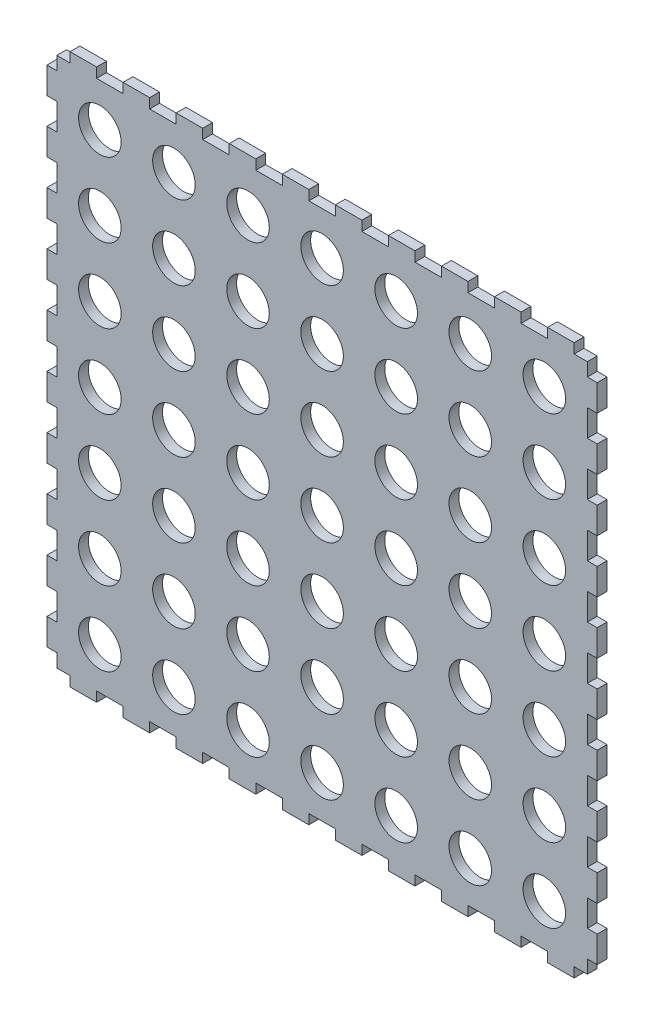
SolidWorks part; units mm, degrees
ref_plane "Front Plane" through (0, 0, 0) normal (0, 0, 1) x (1, 0, 0)
ref_plane "Top Plane" through (0, 0, 0) normal (0, 1, 0) x (1, 0, 0)
ref_plane "Right Plane" through (0, 0, 0) normal (1, 0, 0) x (0, 0, -1)
sketch "Model" plane through (0, 0, 0) normal (0, 0, 1) x (1, 0, 0)
  line L0 (-349.25, 5.6) -> (-349.25, -350) construction
  line L1 (6.35, 5.6) -> (-349.25, 5.6) construction
  line L2 (6.35, -350) -> (6.35, 5.6) construction
  line L3 (-349.25, -350) -> (6.35, -350) construction
  line L4 (-349.25, -350) -> (6.35, 5.6) construction
  line L5 (-350, -172.2) -> (5.6, -172.2) construction
  line L6 (-171.45, -172.581) -> (-171.45, 55.4884) construction
  line L7 (-349.25, -0.75) -> (0, -0.75) construction
  line L8 (-342.9, -343.65) -> (-342.9, 5.6) construction
  line L9 (-349.25, -343.65) -> (0, -343.65) construction
  line L10 (0, -350) -> (0, 5.6) construction
  line L11 (-342.9, -0.75) -> (-334.3275, -0.75)
  line L12 (-334.3275, -0.75) -> (-334.3275, 5.6)
  line L13 (-334.3275, 5.6) -> (-317.1825, 5.6)
  line L14 (-317.1825, 5.6) -> (-317.1825, -0.75)
  line L15 (-317.1825, -0.75) -> (-300.0375, -0.75)
  line L16 (-300.0375, -0.75) -> (-300.0375, 5.6)
  line L17 (-300.0375, 5.6) -> (-282.8925, 5.6)
  line L18 (-282.8925, 5.6) -> (-282.8925, -0.75)
  line L19 (-282.8925, -0.75) -> (-265.7475, -0.75)
  line L20 (-265.7475, -0.75) -> (-265.7475, 5.6)
  line L21 (-265.7475, 5.6) -> (-248.6025, 5.6)
  line L22 (-248.6025, 5.6) -> (-248.6025, -0.75)
  line L23 (-248.6025, -0.75) -> (-231.4575, -0.75)
  line L24 (-231.4575, -0.75) -> (-231.4575, 5.6)
  line L25 (-231.4575, 5.6) -> (-214.3125, 5.6)
  line L26 (-214.3125, 5.6) -> (-214.3125, -0.75)
  line L27 (-214.3125, -0.75) -> (-197.1675, -0.75)
  line L28 (-197.1675, -0.75) -> (-197.1675, 5.6)
  line L29 (-197.1675, 5.6) -> (-180.0225, 5.6)
  line L30 (-180.0225, 5.6) -> (-180.0225, -0.75)
  line L31 (-180.0225, -0.75) -> (-162.8775, -0.75)
  line L32 (-162.8775, -0.75) -> (-162.8775, 5.6)
  line L33 (-162.8775, 5.6) -> (-145.7325, 5.6)
  line L34 (-145.7325, 5.6) -> (-145.7325, -0.75)
  line L35 (-145.7325, -0.75) -> (-128.5875, -0.75)
  line L36 (-128.5875, -0.75) -> (-128.5875, 5.6)
  line L37 (-128.5875, 5.6) -> (-111.4425, 5.6)
  line L38 (-111.4425, 5.6) -> (-111.4425, -0.75)
  line L39 (-111.4425, -0.75) -> (-94.2975, -0.75)
  line L40 (-94.2975, -0.75) -> (-94.2975, 5.6)
  line L41 (-94.2975, 5.6) -> (-77.1525, 5.6)
  line L42 (-77.1525, 5.6) -> (-77.1525, -0.75)
  line L43 (-77.1525, -0.75) -> (-60.0075, -0.75)
  line L44 (-60.0075, -0.75) -> (-60.0075, 5.6)
  line L45 (-60.0075, 5.6) -> (-42.8625, 5.6)
  line L46 (-42.8625, 5.6) -> (-42.8625, -0.75)
  line L47 (-42.8625, -0.75) -> (-25.7175, -0.75)
  line L48 (-25.7175, -0.75) -> (-25.7175, 5.6)
  line L49 (-25.7175, 5.6) -> (-8.5725, 5.6)
  line L50 (-8.5725, 5.6) -> (-8.5725, -0.75)
  line L51 (-8.5725, -0.75) -> (0, -0.75)
  line L52 (-342.9, -0.75) -> (-342.9, -9.3225)
  line L53 (-342.9, -9.3225) -> (-349.25, -9.3225)
  line L54 (-349.25, -9.3225) -> (-349.25, -26.4675)
  line L55 (-349.25, -26.4675) -> (-342.9, -26.4675)
  line L56 (-342.9, -26.4675) -> (-342.9, -43.6125)
  line L57 (-342.9, -43.6125) -> (-349.25, -43.6125)
  line L58 (-349.25, -43.6125) -> (-349.25, -60.7575)
  line L59 (-349.25, -60.7575) -> (-342.9, -60.7575)
  line L60 (-342.9, -60.7575) -> (-342.9, -77.9025)
  line L61 (-342.9, -77.9025) -> (-349.25, -77.9025)
  line L62 (-349.25, -77.9025) -> (-349.25, -95.0475)
  line L63 (-349.25, -95.0475) -> (-342.9, -95.0475)
  line L64 (-342.9, -95.0475) -> (-342.9, -112.1925)
  line L65 (-342.9, -112.1925) -> (-349.25, -112.1925)
  line L66 (-349.25, -112.1925) -> (-349.25, -129.3375)
  line L67 (-349.25, -129.3375) -> (-342.9, -129.3375)
  line L68 (-342.9, -129.3375) -> (-342.9, -146.4825)
  line L69 (-342.9, -146.4825) -> (-349.25, -146.4825)
  line L70 (-349.25, -146.4825) -> (-349.25, -163.6275)
  line L71 (-349.25, -163.6275) -> (-342.9, -163.6275)
  line L72 (-342.9, -163.6275) -> (-342.9, -180.7725)
  line L73 (-342.9, -180.7725) -> (-349.25, -180.7725)
  line L74 (-349.25, -180.7725) -> (-349.25, -197.9175)
  line L75 (-349.25, -197.9175) -> (-342.9, -197.9175)
  line L76 (-342.9, -197.9175) -> (-342.9, -215.0625)
  line L77 (-342.9, -215.0625) -> (-349.25, -215.0625)
  line L78 (-349.25, -215.0625) -> (-349.25, -232.2075)
  line L79 (-349.25, -232.2075) -> (-342.9, -232.2075)
  line L80 (-342.9, -232.2075) -> (-342.9, -249.3525)
  line L81 (-342.9, -249.3525) -> (-349.25, -249.3525)
  line L82 (-349.25, -249.3525) -> (-349.25, -266.4975)
  line L83 (-349.25, -266.4975) -> (-342.9, -266.4975)
  line L84 (-342.9, -266.4975) -> (-342.9, -283.6425)
  line L85 (-342.9, -283.6425) -> (-349.25, -283.6425)
  line L86 (-349.25, -283.6425) -> (-349.25, -300.7875)
  line L87 (-349.25, -300.7875) -> (-342.9, -300.7875)
  line L88 (-342.9, -300.7875) -> (-342.9, -317.9325)
  line L89 (-342.9, -317.9325) -> (-349.25, -317.9325)
  line L90 (-349.25, -317.9325) -> (-349.25, -335.0775)
  line L91 (-349.25, -335.0775) -> (-342.9, -335.0775)
  line L92 (-342.9, -335.0775) -> (-342.9, -343.65)
  line L93 (-342.9, -343.65) -> (-334.3275, -343.65)
  line L94 (-334.3275, -343.65) -> (-334.3275, -350)
  line L95 (-334.3275, -350) -> (-317.1825, -350)
  line L96 (-317.1825, -350) -> (-317.1825, -343.65)
  line L97 (-317.1825, -343.65) -> (-300.0375, -343.65)
  line L98 (-282.8925, -343.65) -> (-265.7475, -343.65)
  line L99 (-282.8925, -350) -> (-282.8925, -343.65)
  line L100 (-300.0375, -350) -> (-282.8925, -350)
  line L101 (-300.0375, -343.65) -> (-300.0375, -350)
  line L102 (-248.6025, -343.65) -> (-231.4575, -343.65)
  line L103 (-248.6025, -350) -> (-248.6025, -343.65)
  line L104 (-265.7475, -350) -> (-248.6025, -350)
  line L105 (-265.7475, -343.65) -> (-265.7475, -350)
  line L106 (-214.3125, -343.65) -> (-197.1675, -343.65)
  line L107 (-214.3125, -350) -> (-214.3125, -343.65)
  line L108 (-231.4575, -350) -> (-214.3125, -350)
  line L109 (-231.4575, -343.65) -> (-231.4575, -350)
  line L110 (-180.0225, -343.65) -> (-162.8775, -343.65)
  line L111 (-180.0225, -350) -> (-180.0225, -343.65)
  line L112 (-197.1675, -350) -> (-180.0225, -350)
  line L113 (-197.1675, -343.65) -> (-197.1675, -350)
  line L114 (-145.7325, -343.65) -> (-128.5875, -343.65)
  line L115 (-145.7325, -350) -> (-145.7325, -343.65)
  line L116 (-162.8775, -350) -> (-145.7325, -350)
  line L117 (-162.8775, -343.65) -> (-162.8775, -350)
  line L118 (-111.4425, -343.65) -> (-94.2975, -343.65)
  line L119 (-111.4425, -350) -> (-111.4425, -343.65)
  line L120 (-128.5875, -350) -> (-111.4425, -350)
  line L121 (-128.5875, -343.65) -> (-128.5875, -350)
  line L122 (-77.1525, -343.65) -> (-60.0075, -343.65)
  line L123 (-77.1525, -350) -> (-77.1525, -343.65)
  line L124 (-94.2975, -350) -> (-77.1525, -350)
  line L125 (-94.2975, -343.65) -> (-94.2975, -350)
  line L126 (-42.8625, -343.65) -> (-25.7175, -343.65)
  line L127 (-42.8625, -350) -> (-42.8625, -343.65)
  line L128 (-60.0075, -350) -> (-42.8625, -350)
  line L129 (-60.0075, -343.65) -> (-60.0075, -350)
  line L130 (-8.5725, -343.65) -> (0, -343.65)
  line L131 (-8.5725, -350) -> (-8.5725, -343.65)
  line L132 (-25.7175, -350) -> (-8.5725, -350)
  line L133 (-25.7175, -343.65) -> (-25.7175, -350)
  line L134 (0, -343.65) -> (0, -335.0775)
  line L135 (0, -335.0775) -> (6.35, -335.0775)
  line L136 (6.35, -335.0775) -> (6.35, -317.9325)
  line L137 (6.35, -317.9325) -> (0, -317.9325)
  line L138 (0, -317.9325) -> (0, -300.7875)
  line L139 (0, -283.6425) -> (0, -266.4975)
  line L140 (6.35, -283.6425) -> (0, -283.6425)
  line L141 (6.35, -300.7875) -> (6.35, -283.6425)
  line L142 (0, -300.7875) -> (6.35, -300.7875)
  line L143 (0, -249.3525) -> (0, -232.2075)
  line L144 (6.35, -249.3525) -> (0, -249.3525)
  line L145 (6.35, -266.4975) -> (6.35, -249.3525)
  line L146 (0, -266.4975) -> (6.35, -266.4975)
  line L147 (0, -215.0625) -> (0, -197.9175)
  line L148 (6.35, -215.0625) -> (0, -215.0625)
  line L149 (6.35, -232.2075) -> (6.35, -215.0625)
  line L150 (0, -232.2075) -> (6.35, -232.2075)
  line L151 (0, -180.7725) -> (0, -163.6275)
  line L152 (6.35, -180.7725) -> (0, -180.7725)
  line L153 (6.35, -197.9175) -> (6.35, -180.7725)
  line L154 (0, -197.9175) -> (6.35, -197.9175)
  line L155 (0, -146.4825) -> (0, -129.3375)
  line L156 (6.35, -146.4825) -> (0, -146.4825)
  line L157 (6.35, -163.6275) -> (6.35, -146.4825)
  line L158 (0, -163.6275) -> (6.35, -163.6275)
  line L159 (0, -112.1925) -> (0, -95.0475)
  line L160 (6.35, -112.1925) -> (0, -112.1925)
  line L161 (6.35, -129.3375) -> (6.35, -112.1925)
  line L162 (0, -129.3375) -> (6.35, -129.3375)
  line L163 (0, -77.9025) -> (0, -60.7575)
  line L164 (6.35, -77.9025) -> (0, -77.9025)
  line L165 (6.35, -95.0475) -> (6.35, -77.9025)
  line L166 (0, -95.0475) -> (6.35, -95.0475)
  line L167 (0, -43.6125) -> (0, -26.4675)
  line L168 (6.35, -43.6125) -> (0, -43.6125)
  line L169 (6.35, -60.7575) -> (6.35, -43.6125)
  line L170 (0, -60.7575) -> (6.35, -60.7575)
  line L171 (0, -0.75) -> (0, -9.3225)
  line L172 (6.35, -9.3225) -> (0, -9.3225)
  line L173 (6.35, -26.4675) -> (6.35, -9.3225)
  line L174 (0, -26.4675) -> (6.35, -26.4675)
  line L175 (0, -9.3225) -> (0, 5.6) [skipped]
  circle A0 centre (-267.208, -28.563) radius 13.75
  circle A1 centre (-219.329, -28.563) radius 13.75
  circle A2 centre (-171.45, -28.563) radius 13.75
  circle A3 centre (-123.571, -28.563) radius 13.75
  circle A4 centre (-75.692, -28.563) radius 13.75
  circle A5 centre (-27.813, -28.563) radius 13.75
  circle A6 centre (-267.208, -76.569) radius 13.75
  circle A7 centre (-219.329, -76.569) radius 13.75
  circle A8 centre (-171.45, -76.569) radius 13.75
  circle A9 centre (-123.571, -76.569) radius 13.75
  circle A10 centre (-75.692, -76.569) radius 13.75
  circle A11 centre (-27.813, -76.569) radius 13.75
  circle A12 centre (-267.208, -124.575) radius 13.75
  circle A13 centre (-219.329, -124.575) radius 13.75
  circle A14 centre (-171.45, -124.575) radius 13.75
  circle A15 centre (-123.571, -124.575) radius 13.75
  circle A16 centre (-75.692, -124.575) radius 13.75
  circle A17 centre (-27.813, -124.575) radius 13.75
  circle A18 centre (-267.208, -172.581) radius 13.75
  circle A19 centre (-219.329, -172.581) radius 13.75
  circle A20 centre (-171.45, -172.581) radius 13.75
  circle A21 centre (-123.571, -172.581) radius 13.75
  circle A22 centre (-75.692, -172.581) radius 13.75
  circle A23 centre (-27.813, -172.581) radius 13.75
  circle A24 centre (-267.208, -220.587) radius 13.75
  circle A25 centre (-219.329, -220.587) radius 13.75
  circle A26 centre (-171.45, -220.587) radius 13.75
  circle A27 centre (-123.571, -220.587) radius 13.75
  circle A28 centre (-75.692, -220.587) radius 13.75
  circle A29 centre (-27.813, -220.587) radius 13.75
  circle A30 centre (-267.208, -268.593) radius 13.75
  circle A31 centre (-219.329, -268.593) radius 13.75
  circle A32 centre (-171.45, -268.593) radius 13.75
  circle A33 centre (-123.571, -268.593) radius 13.75
  circle A34 centre (-75.692, -268.593) radius 13.75
  circle A35 centre (-27.813, -268.593) radius 13.75
  circle A36 centre (-267.208, -316.599) radius 13.75
  circle A37 centre (-219.329, -316.599) radius 13.75
  circle A38 centre (-171.45, -316.599) radius 13.75
  circle A39 centre (-123.571, -316.599) radius 13.75
  circle A40 centre (-75.692, -316.599) radius 13.75
  circle A41 centre (-27.813, -316.599) radius 13.75
  circle A42 centre (-315.087, -76.569) radius 13.75
  circle A43 centre (-315.087, -124.575) radius 13.75
  circle A44 centre (-315.087, -172.581) radius 13.75
  circle A45 centre (-315.087, -220.587) radius 13.75
  circle A46 centre (-315.087, -268.593) radius 13.75
  circle A47 centre (-315.087, -316.599) radius 13.75
  circle A162 centre (-315.087, -28.563) radius 13.75
  dimension "D3" = 27.5
  dimension "D2" = 355.6
  dimension "D4" = 34.163
  dimension "D5" = 34.163
  dimension "D11" = 6.35
  dimension "D12" = 6.35
  dimension "D13" = 6.35
  dimension "D14" = 6.35
  dimension "D15" = 8.5725
  dimension "D16" = 17.145
  dimension "D17" = 17.145
  dimension "D6" = 7
  dimension "D7" = 7
  dimension "D18" = 10
  dimension "D19" = 10
  dimension "D20" = 10
  dimension "D21" = 10
extrude "Boss-Extrude2" add sketch "Model" along normal blind 6.35
